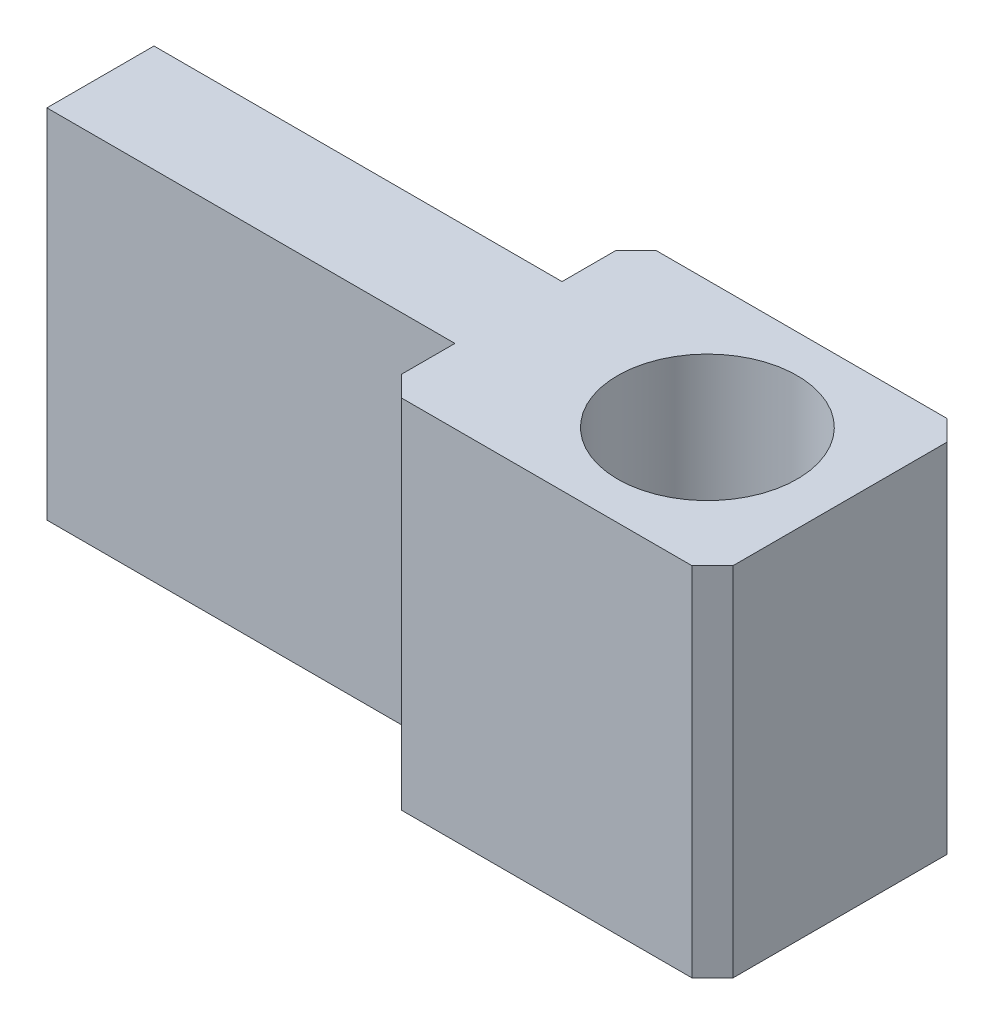
SolidWorks part; units mm, degrees
ref_plane "Front Plane" through (0, 0, 0) normal (0, 0, 1) x (1, 0, 0)
ref_plane "Top Plane" through (0, 0, 0) normal (0, 1, 0) x (1, 0, 0)
ref_plane "Right Plane" through (0, 0, 0) normal (1, 0, 0) x (0, 0, -1)
sketch "Sketch1" plane through (0, 0, 0) normal (0, 1, 0) x (1, 0, 0)
  line L0 (-50.8, 15.875) -> (0, 15.875) construction
  line L1 (0, 0) -> (41.275, 0)
  line L2 (0, 0) -> (0, 31.75)
  line L3 (0, 31.75) -> (41.275, 31.75)
  line L4 (41.275, 0) -> (41.275, 31.75)
  line L5 (0, 22.5425) -> (-50.8, 22.5425)
  line L6 (0, 22.5425) -> (0, 9.2075)
  line L7 (0, 9.2075) -> (-50.8, 9.2075)
  line L8 (-50.8, 22.5425) -> (-50.8, 9.2075)
  dimension "D1" = 41.275
  dimension "D2" = 31.75
  dimension "D3" = 13.335
  dimension "D4" = 50.8
extrude "Boss-Extrude1" add sketch "Sketch1" along normal blind 44.45 contours L1 L4 L3 L2 L6 | L8 L0 L6 L5 | L0 L8 L7 L2
chamfer "Chamfer1" distance 2.54 angle 45 3 edges at (41.275, 22.225, 0) (41.275, 22.225, -31.75) (0, 22.225, 0)
chamfer "Chamfer2" distance 2.54 angle 45 1 edges at (0, 22.225, -31.75)
sketch "Sketch2" plane through (0, 44.45, 0) normal (0, 1, 0) x (1, 0, 0)
  line L0 (41.275, 2.54) -> (41.275, 29.21) construction
  circle A0 centre (24.765, 15.875) radius 11.176
  dimension "D1" = 22.352
  dimension "D2" = 16.51
extrude "Cut-Extrude1" cut sketch "Sketch2" against normal blind 44.45
